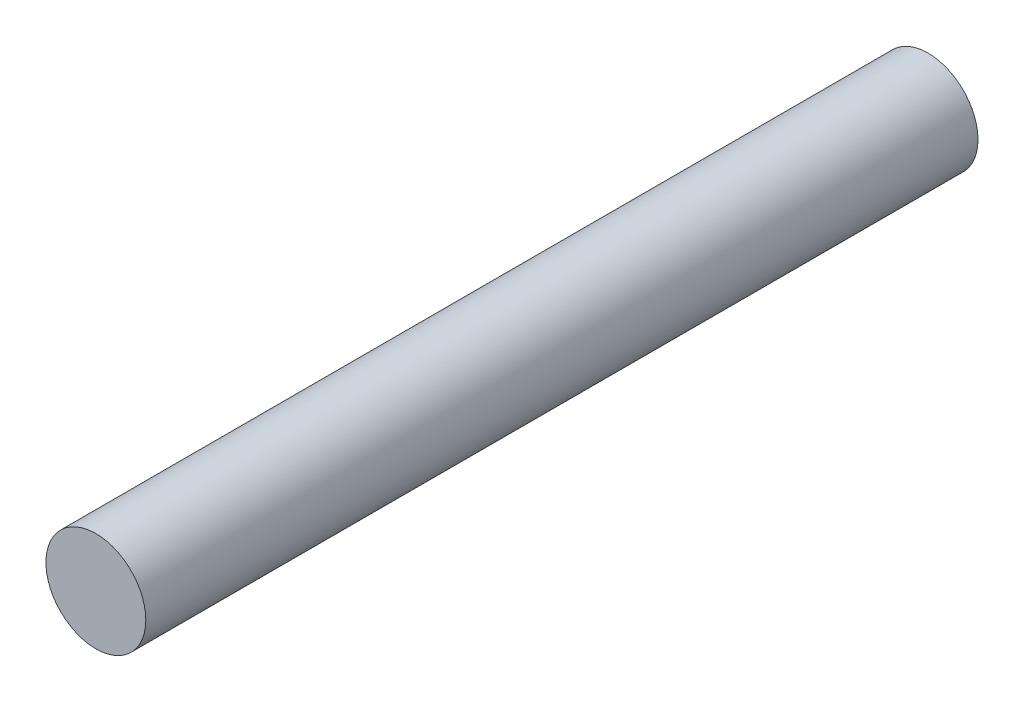
SolidWorks part; units mm, degrees
ref_plane "Front Plane" through (0, 0, 0) normal (0, 0, 1) x (1, 0, 0)
ref_plane "Top Plane" through (0, 0, 0) normal (0, 1, 0) x (1, 0, 0)
ref_plane "Right Plane" through (0, 0, 0) normal (1, 0, 0) x (0, 0, -1)
sketch "Sketch1" plane through (0, 0, 0) normal (0, 0, 1) x (1, 0, 0)
  circle A0 centre (0, 0) radius 1.5
  dimension "D1" = 3
extrude "Boss-Extrude1" add sketch "Sketch1" against normal blind 25 contours A0
